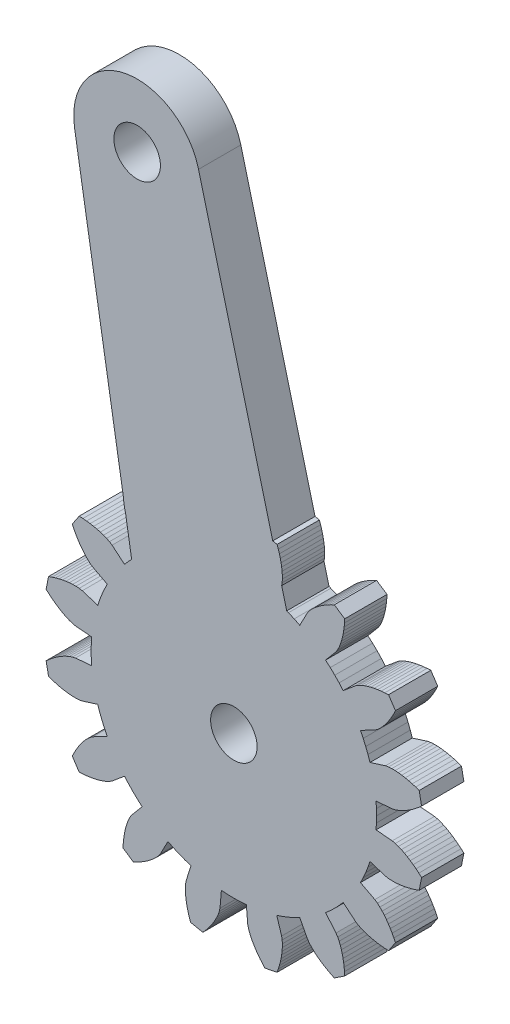
SolidWorks part; units mm, degrees
ref_plane "Спереди" through (0, 0, 0) normal (0, 0, 1) x (1, 0, 0)
ref_plane "Сверху" through (0, 0, 0) normal (0, 1, 0) x (1, 0, 0)
ref_plane "Справа" through (0, 0, 0) normal (1, 0, 0) x (0, 0, -1)
other "Configuration Table"
sketch "Eskiz_kontur" plane through (0, 0, 0) normal (0, 0, 1) x (1, 0, 0)
  line L0 (-1.9137, 0.8842) -> (-1.8847, 0.4425)
  line L1 (-1.8847, 0.4425) -> (-1.875, 0)
  line L2 (-0.7668, 0.9847) -> (-1.9137, 0.8842)
  line L3 (-1.875, 0) -> (-1.8847, -0.4425)
  line L4 (-0.5479, 1.0338) -> (-0.7668, 0.9847)
  line L5 (-1.8847, -0.4425) -> (-1.9137, -0.8842)
  line L6 (-0.3315, 1.1083) -> (-0.5479, 1.0338)
  line L7 (-1.9137, -0.8842) -> (-0.7668, -0.9847)
  line L8 (-0.117, 1.2002) -> (-0.3315, 1.1083)
  line L9 (-0.7668, -0.9847) -> (-0.5479, -1.0338)
  line L10 (0.0954, 1.3068) -> (-0.117, 1.2002)
  line L11 (-0.5479, -1.0338) -> (-0.3315, -1.1083)
  line L12 (0.3057, 1.4266) -> (0.0954, 1.3068)
  line L13 (-0.3315, -1.1083) -> (-0.117, -1.2002)
  line L14 (0.5138, 1.5587) -> (0.3057, 1.4266)
  line L15 (-0.117, -1.2002) -> (0.0954, -1.3068)
  line L16 (0.7195, 1.7023) -> (0.5138, 1.5587)
  line L17 (0.0954, -1.3068) -> (0.3057, -1.4266)
  line L18 (0.9225, 1.857) -> (0.7195, 1.7023)
  line L19 (0.3057, -1.4266) -> (0.5138, -1.5587)
  line L20 (1.1227, 2.0223) -> (0.9225, 1.857)
  line L21 (0.5138, -1.5587) -> (0.7195, -1.7023)
  line L22 (1.3199, 2.1979) -> (1.1227, 2.0223)
  line L23 (0.7195, -1.7023) -> (0.9225, -1.857)
  line L24 (1.1471, 3.0667) -> (1.3199, 2.1979)
  line L25 (0.9225, -1.857) -> (1.1227, -2.0223)
  line L26 (0.8977, 3.1535) -> (1.1471, 3.0667)
  line L27 (1.1227, -2.0223) -> (1.3199, -2.1979)
  line L28 (0.6495, 3.2296) -> (0.8977, 3.1535)
  line L29 (1.3199, -2.1979) -> (1.1471, -3.0667)
  line L30 (0.4027, 3.2948) -> (0.6495, 3.2296)
  line L31 (1.1471, -3.0667) -> (0.8977, -3.1535)
  line L32 (0.1578, 3.3488) -> (0.4027, 3.2948)
  line L33 (0.8977, -3.1535) -> (0.6495, -3.2296)
  line L34 (-0.0851, 3.3912) -> (0.1578, 3.3488)
  line L35 (0.6495, -3.2296) -> (0.4027, -3.2948)
  line L36 (-0.3252, 3.4214) -> (-0.0851, 3.3912)
  line L37 (0.4027, -3.2948) -> (0.1578, -3.3488)
  line L38 (-0.5623, 3.4386) -> (-0.3252, 3.4214)
  line L39 (0.1578, -3.3488) -> (-0.0851, -3.3912)
  line L40 (-0.7956, 3.4415) -> (-0.5623, 3.4386)
  line L41 (-0.0851, -3.3912) -> (-0.3252, -3.4214)
  line L42 (-1.024, 3.4274) -> (-0.7956, 3.4415)
  line L43 (-0.3252, -3.4214) -> (-0.5623, -3.4386)
  line L44 (-1.245, 3.389) -> (-1.024, 3.4274)
  line L45 (-0.5623, -3.4386) -> (-0.7956, -3.4415)
  line L46 (-2.3431, 3.043) -> (-1.245, 3.389)
  line L47 (-0.7956, -3.4415) -> (-1.024, -3.4274)
  line L48 (-2.4853, 3.4621) -> (-2.3431, 3.043)
  line L49 (-1.024, -3.4274) -> (-1.245, -3.389)
  line L50 (-2.6457, 3.8747) -> (-2.4853, 3.4621)
  line L51 (-1.245, -3.389) -> (-2.3431, -3.043)
  line L52 (-2.824, 4.2798) -> (-2.6457, 3.8747)
  line L53 (-2.3431, -3.043) -> (-2.4853, -3.4621)
  line L54 (-3.0198, 4.6767) -> (-2.824, 4.2798)
  line L55 (-2.4853, -3.4621) -> (-2.6457, -3.8747)
  line L56 (-1.9987, 5.2085) -> (-3.0198, 4.6767)
  line L57 (-2.6457, -3.8747) -> (-2.824, -4.2798)
  line L58 (-1.8152, 5.3376) -> (-1.9987, 5.2085)
  line L59 (-2.824, -4.2798) -> (-3.0198, -4.6767)
  line L60 (-1.6438, 5.4893) -> (-1.8152, 5.3376)
  line L61 (-3.0198, -4.6767) -> (-1.9987, -5.2085)
  line L62 (-1.4808, 5.6562) -> (-1.6438, 5.4893)
  line L63 (-1.9987, -5.2085) -> (-1.8152, -5.3376)
  line L64 (-1.3254, 5.836) -> (-1.4808, 5.6562)
  line L65 (-1.8152, -5.3376) -> (-1.6438, -5.4893)
  line L66 (-1.1769, 6.0272) -> (-1.3254, 5.836)
  line L67 (-1.6438, -5.4893) -> (-1.4808, -5.6562)
  line L68 (-1.0352, 6.2289) -> (-1.1769, 6.0272)
  line L69 (-1.4808, -5.6562) -> (-1.3254, -5.836)
  line L70 (-0.9002, 6.4403) -> (-1.0352, 6.2289)
  line L71 (-1.3254, -5.836) -> (-1.1769, -6.0272)
  line L72 (-0.7718, 6.6609) -> (-0.9002, 6.4403)
  line L73 (-1.1769, -6.0272) -> (-1.0352, -6.2289)
  line L74 (-0.6501, 6.8902) -> (-0.7718, 6.6609)
  line L75 (-1.0352, -6.2289) -> (-0.9002, -6.4403)
  line L76 (-0.5351, 7.1279) -> (-0.6501, 6.8902)
  line L77 (-0.9002, -6.4403) -> (-0.7718, -6.6609)
  line L78 (-1.0273, 7.8645) -> (-0.5351, 7.1279)
  line L79 (-0.7718, -6.6609) -> (-0.6501, -6.8902)
  line L80 (-1.2909, 7.8492) -> (-1.0273, 7.8645)
  line L81 (-0.6501, -6.8902) -> (-0.5351, -7.1279)
  line L82 (-1.5493, 7.8245) -> (-1.2909, 7.8492)
  line L83 (-0.5351, -7.1279) -> (-1.0273, -7.8645)
  line L84 (-1.8022, 7.7903) -> (-1.5493, 7.8245)
  line L85 (-1.0273, -7.8645) -> (-1.2909, -7.8492)
  line L86 (-2.0492, 7.7465) -> (-1.8022, 7.7903)
  line L87 (-1.2909, -7.8492) -> (-1.5493, -7.8245)
  line L88 (-2.2898, 7.6927) -> (-2.0492, 7.7465)
  line L89 (-1.5493, -7.8245) -> (-1.8022, -7.7903)
  line L90 (-2.5232, 7.6287) -> (-2.2898, 7.6927)
  line L91 (-1.8022, -7.7903) -> (-2.0492, -7.7465)
  line L92 (-2.7488, 7.5539) -> (-2.5232, 7.6287)
  line L93 (-2.0492, -7.7465) -> (-2.2898, -7.6927)
  line L94 (-2.9654, 7.4672) -> (-2.7488, 7.5539)
  line L95 (-2.2898, -7.6927) -> (-2.5232, -7.6287)
  line L96 (-3.1711, 7.3669) -> (-2.9654, 7.4672)
  line L97 (-2.5232, -7.6287) -> (-2.7488, -7.5539)
  line L98 (-3.3606, 7.2468) -> (-3.1711, 7.3669)
  line L99 (-2.7488, -7.5539) -> (-2.9654, -7.4672)
  line L100 (-4.2427, 6.5069) -> (-3.3606, 7.2468)
  line L101 (-2.9654, -7.4672) -> (-3.1711, -7.3669)
  line L102 (-4.5345, 6.8397) -> (-4.2427, 6.5069)
  line L103 (-3.1711, -7.3669) -> (-3.3606, -7.2468)
  line L104 (-4.8405, 7.1595) -> (-4.5345, 6.8397)
  line L105 (-3.3606, -7.2468) -> (-4.2427, -6.5069)
  line L106 (-5.1603, 7.4655) -> (-4.8405, 7.1595)
  line L107 (-4.2427, -6.5069) -> (-4.5345, -6.8397)
  line L108 (-5.4931, 7.7573) -> (-5.1603, 7.4655)
  line L109 (-4.5345, -6.8397) -> (-4.8405, -7.1595)
  line L110 (-4.7532, 8.6394) -> (-5.4931, 7.7573)
  line L111 (-4.8405, -7.1595) -> (-5.1603, -7.4655)
  line L112 (-4.6331, 8.8289) -> (-4.7532, 8.6394)
  line L113 (-5.1603, -7.4655) -> (-5.4931, -7.7573)
  line L114 (-4.5328, 9.0346) -> (-4.6331, 8.8289)
  line L115 (-5.4931, -7.7573) -> (-4.7532, -8.6394)
  line L116 (-4.4461, 9.2512) -> (-4.5328, 9.0346)
  line L117 (-4.7532, -8.6394) -> (-4.6331, -8.8289)
  line L118 (-4.3713, 9.4768) -> (-4.4461, 9.2512)
  line L119 (-4.6331, -8.8289) -> (-4.5328, -9.0346)
  line L120 (-4.3073, 9.7102) -> (-4.3713, 9.4768)
  line L121 (-4.5328, -9.0346) -> (-4.4461, -9.2512)
  line L122 (-4.2535, 9.9508) -> (-4.3073, 9.7102)
  line L123 (-4.4461, -9.2512) -> (-4.3713, -9.4768)
  line L124 (-4.2097, 10.1977) -> (-4.2535, 9.9508)
  line L125 (-4.3713, -9.4768) -> (-4.3073, -9.7102)
  line L126 (-4.1755, 10.4507) -> (-4.2097, 10.1977)
  line L127 (-4.3073, -9.7102) -> (-4.2535, -9.9508)
  line L128 (-4.1508, 10.7091) -> (-4.1755, 10.4507)
  line L129 (-4.2535, -9.9508) -> (-4.2097, -10.1977)
  line L130 (-4.1355, 10.9727) -> (-4.1508, 10.7091)
  line L131 (-4.2097, -10.1977) -> (-4.1755, -10.4507)
  line L132 (-4.8721, 11.4649) -> (-4.1355, 10.9727)
  line L133 (-4.1755, -10.4507) -> (-4.1508, -10.7091)
  line L134 (-5.1098, 11.3499) -> (-4.8721, 11.4649)
  line L135 (-4.1508, -10.7091) -> (-4.1355, -10.9727)
  line L136 (-5.3391, 11.2282) -> (-5.1098, 11.3499)
  line L137 (-4.1355, -10.9727) -> (-4.8721, -11.4649)
  line L138 (-5.5597, 11.0998) -> (-5.3391, 11.2282)
  line L139 (-4.8721, -11.4649) -> (-5.1098, -11.3499)
  line L140 (-5.7711, 10.9648) -> (-5.5597, 11.0998)
  line L141 (-5.1098, -11.3499) -> (-5.3391, -11.2282)
  line L142 (-5.9728, 10.8231) -> (-5.7711, 10.9648)
  line L143 (-5.3391, -11.2282) -> (-5.5597, -11.0998)
  line L144 (-6.164, 10.6746) -> (-5.9728, 10.8231)
  line L145 (-5.5597, -11.0998) -> (-5.7711, -10.9648)
  line L146 (-6.3438, 10.5191) -> (-6.164, 10.6746)
  line L147 (-5.7711, -10.9648) -> (-5.9728, -10.8231)
  line L148 (-6.5107, 10.3562) -> (-6.3438, 10.5191)
  line L149 (-5.9728, -10.8231) -> (-6.164, -10.6746)
  line L150 (-6.6624, 10.1848) -> (-6.5107, 10.3562)
  line L151 (-6.164, -10.6746) -> (-6.3438, -10.5191)
  line L152 (-6.7915, 10.0013) -> (-6.6624, 10.1848)
  line L153 (-6.3438, -10.5191) -> (-6.5107, -10.3562)
  line L154 (-7.3233, 8.9802) -> (-6.7915, 10.0013)
  line L155 (-6.5107, -10.3562) -> (-6.6624, -10.1848)
  line L156 (-7.7202, 9.176) -> (-7.3233, 8.9802)
  line L157 (-6.6624, -10.1848) -> (-6.7915, -10.0013)
  line L158 (-8.1253, 9.3543) -> (-7.7202, 9.176)
  line L159 (-6.7915, -10.0013) -> (-7.3233, -8.9802)
  line L160 (-8.2498, 9.4027) -> (-8.1253, 9.3543)
  line L161 (-7.3233, -8.9802) -> (-7.7202, -9.176)
  line L162 (-8.6075, 10.7753) -> (-8.2498, 9.4027)
  line L163 (-7.7202, -9.176) -> (-8.1253, -9.3543)
  line L164 (-8.5725, 10.976) -> (-8.6075, 10.7753)
  line L165 (-8.1253, -9.3543) -> (-8.5379, -9.5147)
  line L166 (-8.5585, 11.2044) -> (-8.5725, 10.976)
  line L167 (-8.5379, -9.5147) -> (-8.957, -9.6569)
  line L168 (-8.5614, 11.4377) -> (-8.5585, 11.2044)
  line L169 (-8.957, -9.6569) -> (-8.611, -10.755)
  line L170 (-8.5786, 11.6748) -> (-8.5614, 11.4377)
  line L171 (-8.611, -10.755) -> (-8.5725, -10.976)
  line L172 (-8.6088, 11.9149) -> (-8.5786, 11.6748)
  line L173 (-8.5725, -10.976) -> (-8.5585, -11.2044)
  line L174 (-8.6512, 12.1578) -> (-8.6088, 11.9149)
  line L175 (-8.5585, -11.2044) -> (-8.5614, -11.4377)
  line L176 (-8.7052, 12.4027) -> (-8.6512, 12.1578)
  line L177 (-8.5614, -11.4377) -> (-8.5786, -11.6748)
  line L178 (-8.7704, 12.6495) -> (-8.7052, 12.4027)
  line L179 (-8.5786, -11.6748) -> (-8.6088, -11.9149)
  line L180 (-8.8465, 12.8977) -> (-8.7704, 12.6495)
  line L181 (-8.6088, -11.9149) -> (-8.6512, -12.1578)
  line L182 (-8.9333, 13.1471) -> (-8.8465, 12.8977)
  line L183 (-8.6512, -12.1578) -> (-8.7052, -12.4027)
  line L184 (-9.2415, 13.2084) -> (-8.9333, 13.1471)
  line L185 (-8.7052, -12.4027) -> (-8.7704, -12.6495)
  line L186 (-14.5044, 33.4056) -> (-9.2415, 13.2084)
  line L187 (-8.7704, -12.6495) -> (-8.8465, -12.8977)
  line L188 (-8.8465, -12.8977) -> (-8.9333, -13.1471)
  line L189 (-19.8434, 10.6485) -> (-23.2994, 31.5362)
  line L190 (-8.9333, -13.1471) -> (-9.8021, -13.3199)
  line L191 (-19.8245, 10.4507) -> (-19.8434, 10.6485)
  line L192 (-9.8021, -13.3199) -> (-9.9777, -13.1227)
  line L193 (-19.7903, 10.1977) -> (-19.8245, 10.4507)
  line L194 (-9.9777, -13.1227) -> (-10.143, -12.9225)
  line L195 (-19.7465, 9.9508) -> (-19.7903, 10.1977)
  line L196 (-10.143, -12.9225) -> (-10.2977, -12.7195)
  line L197 (-19.6927, 9.7102) -> (-19.7465, 9.9508)
  line L198 (-10.2977, -12.7195) -> (-10.4413, -12.5138)
  line L199 (-19.6812, 9.6683) -> (-19.6927, 9.7102)
  line L200 (-10.4413, -12.5138) -> (-10.5734, -12.3057)
  line L201 (-19.2504, 7.0644) -> (-19.6812, 9.6683)
  line L202 (-10.5734, -12.3057) -> (-10.6932, -12.0954)
  line L203 (-19.4655, 6.8397) -> (-19.2504, 7.0644)
  line L204 (-10.6932, -12.0954) -> (-10.7998, -11.883)
  line L205 (-19.7573, 6.5069) -> (-19.4655, 6.8397)
  line L206 (-10.7998, -11.883) -> (-10.8917, -11.6685)
  line L207 (-20.6394, 7.2468) -> (-19.7573, 6.5069)
  line L208 (-10.8917, -11.6685) -> (-10.9662, -11.4521)
  line L209 (-20.8289, 7.3669) -> (-20.6394, 7.2468)
  line L210 (-10.9662, -11.4521) -> (-11.0153, -11.2332)
  line L211 (-21.0346, 7.4672) -> (-20.8289, 7.3669)
  line L212 (-11.0153, -11.2332) -> (-11.1158, -10.0863)
  line L213 (-21.2512, 7.5539) -> (-21.0346, 7.4672)
  line L214 (-11.1158, -10.0863) -> (-11.5575, -10.1153)
  line L215 (-21.4768, 7.6287) -> (-21.2512, 7.5539)
  line L216 (-11.5575, -10.1153) -> (-12, -10.125)
  line L217 (-21.7102, 7.6927) -> (-21.4768, 7.6287)
  line L218 (-12, -10.125) -> (-12.4425, -10.1153)
  line L219 (-21.9508, 7.7465) -> (-21.7102, 7.6927)
  line L220 (-12.4425, -10.1153) -> (-12.8842, -10.0863)
  line L221 (-22.1977, 7.7903) -> (-21.9508, 7.7465)
  line L222 (-12.8842, -10.0863) -> (-12.9847, -11.2332)
  line L223 (-22.4507, 7.8245) -> (-22.1977, 7.7903)
  line L224 (-12.9847, -11.2332) -> (-13.0338, -11.4521)
  line L225 (-22.7091, 7.8492) -> (-22.4507, 7.8245)
  line L226 (-13.0338, -11.4521) -> (-13.1083, -11.6685)
  line L227 (-22.9727, 7.8645) -> (-22.7091, 7.8492)
  line L228 (-13.1083, -11.6685) -> (-13.2002, -11.883)
  line L229 (-23.4649, 7.1279) -> (-22.9727, 7.8645)
  line L230 (-13.2002, -11.883) -> (-13.3068, -12.0954)
  line L231 (-23.3499, 6.8902) -> (-23.4649, 7.1279)
  line L232 (-13.3068, -12.0954) -> (-13.4266, -12.3057)
  line L233 (-23.2282, 6.6609) -> (-23.3499, 6.8902)
  line L234 (-13.4266, -12.3057) -> (-13.5587, -12.5138)
  line L235 (-23.0998, 6.4403) -> (-23.2282, 6.6609)
  line L236 (-13.5587, -12.5138) -> (-13.7023, -12.7195)
  line L237 (-22.9648, 6.2289) -> (-23.0998, 6.4403)
  line L238 (-13.7023, -12.7195) -> (-13.857, -12.9225)
  line L239 (-22.8231, 6.0272) -> (-22.9648, 6.2289)
  line L240 (-13.857, -12.9225) -> (-14.0223, -13.1227)
  line L241 (-22.6746, 5.836) -> (-22.8231, 6.0272)
  line L242 (-14.0223, -13.1227) -> (-14.1979, -13.3199)
  line L243 (-22.5191, 5.6562) -> (-22.6746, 5.836)
  line L244 (-14.1979, -13.3199) -> (-15.0667, -13.1471)
  line L245 (-22.3562, 5.4893) -> (-22.5191, 5.6562)
  line L246 (-15.0667, -13.1471) -> (-15.1535, -12.8977)
  line L247 (-22.1848, 5.3376) -> (-22.3562, 5.4893)
  line L248 (-15.1535, -12.8977) -> (-15.2296, -12.6495)
  line L249 (-22.0013, 5.2085) -> (-22.1848, 5.3376)
  line L250 (-15.2296, -12.6495) -> (-15.2948, -12.4027)
  line L251 (-20.9802, 4.6767) -> (-22.0013, 5.2085)
  line L252 (-15.2948, -12.4027) -> (-15.3488, -12.1578)
  line L253 (-21.176, 4.2798) -> (-20.9802, 4.6767)
  line L254 (-15.3488, -12.1578) -> (-15.3912, -11.9149)
  line L255 (-21.3543, 3.8747) -> (-21.176, 4.2798)
  line L256 (-15.3912, -11.9149) -> (-15.4214, -11.6748)
  line L257 (-21.5147, 3.4621) -> (-21.3543, 3.8747)
  line L258 (-15.4214, -11.6748) -> (-15.4386, -11.4377)
  line L259 (-21.6569, 3.043) -> (-21.5147, 3.4621)
  line L260 (-15.4386, -11.4377) -> (-15.4415, -11.2044)
  line L261 (-22.755, 3.389) -> (-21.6569, 3.043)
  line L262 (-15.4415, -11.2044) -> (-15.4275, -10.976)
  line L263 (-22.976, 3.4274) -> (-22.755, 3.389)
  line L264 (-15.4275, -10.976) -> (-15.389, -10.755)
  line L265 (-23.2044, 3.4415) -> (-22.976, 3.4274)
  line L266 (-15.389, -10.755) -> (-15.043, -9.6569)
  line L267 (-23.4377, 3.4386) -> (-23.2044, 3.4415)
  line L268 (-15.043, -9.6569) -> (-15.4621, -9.5147)
  line L269 (-23.6748, 3.4214) -> (-23.4377, 3.4386)
  line L270 (-15.4621, -9.5147) -> (-15.8747, -9.3543)
  line L271 (-23.915, 3.3912) -> (-23.6748, 3.4214)
  line L272 (-15.8747, -9.3543) -> (-16.2798, -9.176)
  line L273 (-24.1578, 3.3488) -> (-23.915, 3.3912)
  line L274 (-16.2798, -9.176) -> (-16.6767, -8.9802)
  line L275 (-24.4027, 3.2948) -> (-24.1578, 3.3488)
  line L276 (-16.6767, -8.9802) -> (-17.2085, -10.0013)
  line L277 (-24.6495, 3.2296) -> (-24.4027, 3.2948)
  line L278 (-17.2085, -10.0013) -> (-17.3376, -10.1848)
  line L279 (-24.8977, 3.1535) -> (-24.6495, 3.2296)
  line L280 (-17.3376, -10.1848) -> (-17.4892, -10.3562)
  line L281 (-25.1471, 3.0667) -> (-24.8977, 3.1535)
  line L282 (-17.4892, -10.3562) -> (-17.6562, -10.5191)
  line L283 (-25.3199, 2.1979) -> (-25.1471, 3.0667)
  line L284 (-17.6562, -10.5191) -> (-17.836, -10.6746)
  line L285 (-25.1227, 2.0223) -> (-25.3199, 2.1979)
  line L286 (-17.836, -10.6746) -> (-18.0272, -10.8231)
  line L287 (-24.9225, 1.857) -> (-25.1227, 2.0223)
  line L288 (-18.0272, -10.8231) -> (-18.2289, -10.9648)
  line L289 (-24.7195, 1.7023) -> (-24.9225, 1.857)
  line L290 (-18.2289, -10.9648) -> (-18.4403, -11.0998)
  line L291 (-24.5138, 1.5587) -> (-24.7195, 1.7023)
  line L292 (-18.4403, -11.0998) -> (-18.6609, -11.2282)
  line L293 (-24.3057, 1.4266) -> (-24.5138, 1.5587)
  line L294 (-18.6609, -11.2282) -> (-18.8902, -11.3499)
  line L295 (-24.0954, 1.3068) -> (-24.3057, 1.4266)
  line L296 (-18.8902, -11.3499) -> (-19.1279, -11.4649)
  line L297 (-23.883, 1.2002) -> (-24.0954, 1.3068)
  line L298 (-19.1279, -11.4649) -> (-19.8645, -10.9727)
  line L299 (-23.6685, 1.1083) -> (-23.883, 1.2002)
  line L300 (-19.8645, -10.9727) -> (-19.8492, -10.7091)
  line L301 (-23.4521, 1.0338) -> (-23.6685, 1.1083)
  line L302 (-19.8492, -10.7091) -> (-19.8245, -10.4507)
  line L303 (-23.2332, 0.9847) -> (-23.4521, 1.0338)
  line L304 (-19.8245, -10.4507) -> (-19.7903, -10.1977)
  line L305 (-22.0863, 0.8842) -> (-23.2332, 0.9847)
  line L306 (-19.7903, -10.1977) -> (-19.7465, -9.9508)
  line L307 (-22.1153, 0.4425) -> (-22.0863, 0.8842)
  line L308 (-19.7465, -9.9508) -> (-19.6927, -9.7102)
  line L309 (-22.125, 0) -> (-22.1153, 0.4425)
  line L310 (-19.6927, -9.7102) -> (-19.6287, -9.4768)
  line L311 (-22.1153, -0.4425) -> (-22.125, 0)
  line L312 (-19.6287, -9.4768) -> (-19.5539, -9.2512)
  line L313 (-22.0863, -0.8842) -> (-22.1153, -0.4425)
  line L314 (-19.5539, -9.2512) -> (-19.4672, -9.0346)
  line L315 (-23.2332, -0.9847) -> (-22.0863, -0.8842)
  line L316 (-19.4672, -9.0346) -> (-19.3669, -8.8289)
  line L317 (-23.4521, -1.0338) -> (-23.2332, -0.9847)
  line L318 (-19.3669, -8.8289) -> (-19.2468, -8.6394)
  line L319 (-23.6685, -1.1083) -> (-23.4521, -1.0338)
  line L320 (-19.2468, -8.6394) -> (-18.5069, -7.7573)
  line L321 (-23.883, -1.2002) -> (-23.6685, -1.1083)
  line L322 (-18.5069, -7.7573) -> (-18.8397, -7.4655)
  line L323 (-24.0954, -1.3068) -> (-23.883, -1.2002)
  line L324 (-18.8397, -7.4655) -> (-19.1595, -7.1595)
  line L325 (-24.3057, -1.4266) -> (-24.0954, -1.3068)
  line L326 (-19.1595, -7.1595) -> (-19.4655, -6.8397)
  line L327 (-24.5138, -1.5587) -> (-24.3057, -1.4266)
  line L328 (-19.4655, -6.8397) -> (-19.7573, -6.5069)
  line L329 (-24.7195, -1.7023) -> (-24.5138, -1.5587)
  line L330 (-19.7573, -6.5069) -> (-20.6394, -7.2468)
  line L331 (-24.9225, -1.857) -> (-24.7195, -1.7023)
  line L332 (-20.6394, -7.2468) -> (-20.8289, -7.3669)
  line L333 (-25.1227, -2.0223) -> (-24.9225, -1.857)
  line L334 (-20.8289, -7.3669) -> (-21.0346, -7.4672)
  line L335 (-25.3199, -2.1979) -> (-25.1227, -2.0223)
  line L336 (-21.0346, -7.4672) -> (-21.2512, -7.5539)
  line L337 (-25.1471, -3.0667) -> (-25.3199, -2.1979)
  line L338 (-21.2512, -7.5539) -> (-21.4768, -7.6287)
  line L339 (-24.8977, -3.1535) -> (-25.1471, -3.0667)
  line L340 (-21.4768, -7.6287) -> (-21.7102, -7.6927)
  line L341 (-24.6495, -3.2296) -> (-24.8977, -3.1535)
  line L342 (-21.7102, -7.6927) -> (-21.9508, -7.7465)
  line L343 (-24.4027, -3.2948) -> (-24.6495, -3.2296)
  line L344 (-21.9508, -7.7465) -> (-22.1977, -7.7903)
  line L345 (-24.1578, -3.3488) -> (-24.4027, -3.2948)
  line L346 (-22.1977, -7.7903) -> (-22.4507, -7.8245)
  line L347 (-23.915, -3.3912) -> (-24.1578, -3.3488)
  line L348 (-22.4507, -7.8245) -> (-22.7091, -7.8492)
  line L349 (-23.6748, -3.4214) -> (-23.915, -3.3912)
  line L350 (-22.7091, -7.8492) -> (-22.9727, -7.8645)
  line L351 (-23.4377, -3.4386) -> (-23.6748, -3.4214)
  line L352 (-22.9727, -7.8645) -> (-23.4649, -7.1279)
  line L353 (-23.2044, -3.4415) -> (-23.4377, -3.4386)
  line L354 (-23.4649, -7.1279) -> (-23.3499, -6.8902)
  line L355 (-22.976, -3.4274) -> (-23.2044, -3.4415)
  line L356 (-23.3499, -6.8902) -> (-23.2282, -6.6609)
  line L357 (-22.755, -3.389) -> (-22.976, -3.4274)
  line L358 (-23.2282, -6.6609) -> (-23.0998, -6.4403)
  line L359 (-21.6569, -3.043) -> (-22.755, -3.389)
  line L360 (-23.0998, -6.4403) -> (-22.9648, -6.2289)
  line L361 (-21.5147, -3.4621) -> (-21.6569, -3.043)
  line L362 (-22.9648, -6.2289) -> (-22.8231, -6.0272)
  line L363 (-21.3543, -3.8747) -> (-21.5147, -3.4621)
  line L364 (-22.8231, -6.0272) -> (-22.6746, -5.836)
  line L365 (-21.176, -4.2798) -> (-21.3543, -3.8747)
  line L366 (-22.6746, -5.836) -> (-22.5191, -5.6562)
  line L367 (-20.9802, -4.6767) -> (-21.176, -4.2798)
  line L368 (-22.5191, -5.6562) -> (-22.3562, -5.4893)
  line L369 (-22.0013, -5.2085) -> (-20.9802, -4.6767)
  line L370 (-22.3562, -5.4893) -> (-22.1848, -5.3376)
  line L371 (-22.1848, -5.3376) -> (-22.0013, -5.2085)
  arc A0 (-23.2994, 31.5362) -> (-14.5044, 33.4056) centre (-18.8611, 32.2789) cw
extrude "Plastina" add sketch "Eskiz_kontur" along normal blind 3
sketch "Eskiz_otverstiya" plane through (0, 0, 0) normal (0, 0, 1) x (1, 0, 0)
  circle A0 centre (-12, 0) radius 1.65
  circle A1 centre (-18.8611, 32.2789) radius 1.65
  dimension "d1" = 3.3
  dimension "d2" = 3.3
extrude "Otverstiya" cut sketch "Eskiz_otverstiya" against normal through all and the other way through all
equation "\"T3\" = 3"
equation "\"T5\" = 5"
equation "\"D_M3\" = 3.3"
equation "\"D_M2\" = 2.2"
equation "\"D_M3_TAP\" = 2.5"
equation "\"D_M4\" = 4.5"
equation "\"L1\" = 100"
equation "\"L2\" = 100"
equation "\"D1@Plastina\" = \"T3\""
equation "\"d1@Eskiz_otverstiya\" = \"D_M3\""
equation "\"d2@Eskiz_otverstiya\" = \"D_M3\""
